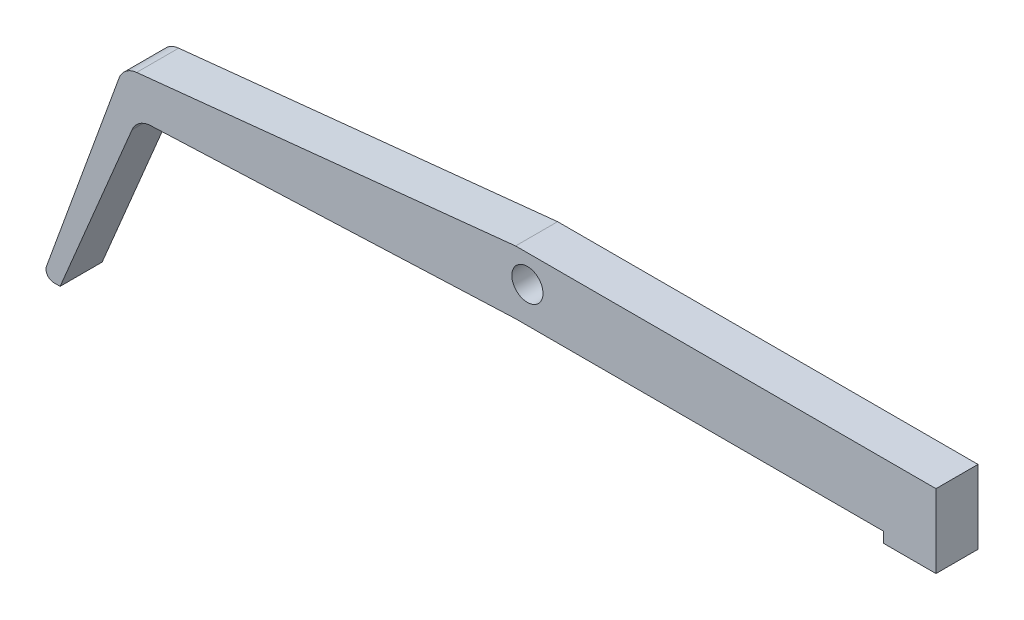
SolidWorks part; units mm, degrees
ref_plane "Front Plane" through (0, 0, 0) normal (0, 0, 1) x (1, 0, 0)
ref_plane "Top Plane" through (0, 0, 0) normal (0, 1, 0) x (1, 0, 0)
ref_plane "Right Plane" through (0, 0, 0) normal (1, 0, 0) x (0, 0, -1)
sketch "Sketch4" plane through (0, 0, 0) normal (0, 0, 1) x (1, 0, 0)
  line L0 (-92.2532, 38.75) -> (77.7468, 38.75) construction
  line L1 (77.7468, 38.75) -> (77.7468, -11.25) construction
  line L2 (77.7468, -11.25) -> (-92.2532, -11.25) construction
  line L3 (-92.2532, -11.25) -> (-92.2532, 38.75) construction
  line L4 (77.7468, 38.75) -> (-2.2532, 38.75)
  line L5 (-2.2532, 38.75) -> (-76.8552, 31.0336)
  line L6 (-76.8552, 31.0336) -> (-92.2532, -11.25)
  line L7 (77.7468, 38.75) -> (77.7468, 26.75)
  line L8 (77.7468, 26.75) -> (-2.2532, 26.75)
  line L9 (-2.2532, 26.75) -> (-74.2532, 23.75)
  line L11 (-74.2532, 23.75) -> (-88.9232, -11.25)
  line L12 (-88.9232, -11.25) -> (-92.2532, -11.25)
  dimension "D1" = 170
  dimension "D2" = 50
  dimension "D3" = 80
  dimension "D4" = 75
  dimension "D5" = 45
  dimension "D6" = 12
  dimension "D7" = 80
  dimension "D8" = 72
  dimension "D9" = 3.33
extrude "Boss-Extrude1" add sketch "Sketch4" along normal blind 8
sketch "Sketch6" plane through (0, 26.75, 0) normal (0, -1, 0) x (1, 0, 0)
  line L0 (77.7468, 8) -> (67.7468, 8)
  line L1 (77.7468, 8) -> (77.7468, 6.4)
  line L2 (67.7468, 8) -> (67.7468, 6.4)
  line L3 (77.7468, 6.4) -> (67.7468, 6.4)
  line L4 (-2.2532, 8) -> (77.7468, 8) construction
  line L5 (77.7468, 4) -> (66.0053, 4) construction
  line L6 (77.7468, 8) -> (77.7468, 0) construction
  line L7 (77.7468, 6.4) -> (76.1468, 6.4)
  line L8 (77.7468, 6.4) -> (77.7468, 1.6)
  line L9 (76.1468, 6.4) -> (76.1468, 1.6)
  line L10 (77.7468, 4) -> (76.1468, 4)
  line L11 (77.7468, 0) -> (77.7468, 1.6)
  line L12 (77.7468, 1.6) -> (67.7468, 1.6)
  line L13 (77.7468, 0) -> (67.7468, 0)
  line L14 (67.7468, 0) -> (67.7468, 1.6)
  line M9 (-2.2532, 0) -> (77.7468, 0)
  line M10 (77.7468, 0) -> (77.7468, 8)
  line M11 (77.7468, 8) -> (-2.2532, 8)
  dimension "D1" = 10
  dimension "D2" = 1.6
  dimension "D3" = 1.6
extrude "Boss-Extrude2" add sketch "Sketch6" along normal blind 2 contours L3 L2 M10 M11 | L10 L8 L3 L9 | L12 L10 L9 M10 | L14 L12 M9 M10
fillet "Fillet1" radius 4 2 edges at (-74.2532, 23.75, 4) (-76.8552, 31.0336, 4)
sketch "Sketch7" plane through (0, 0, 8) normal (0, 0, 1) x (1, 0, 0)
  circle A0 centre (0, 33.5329) radius 2.9665
extrude "Cut-Extrude1" cut sketch "Sketch7" against normal through all both and the other way through all
fillet "Fillet3" radius 1.5 1 edges at (-92.2532, -11.25, 4)
